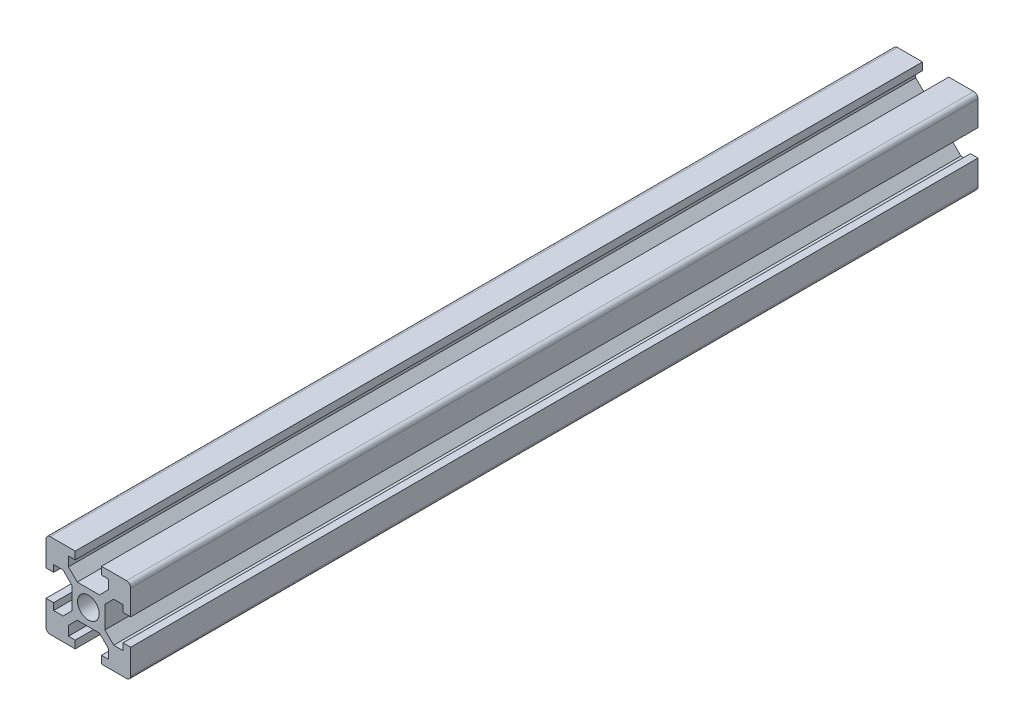
SolidWorks part; units mm, degrees
ref_plane "前视基准面" through (0, 0, 0) normal (0, 0, 1) x (1, 0, 0)
ref_plane "上视基准面" through (0, 0, 0) normal (0, 1, 0) x (1, 0, 0)
ref_plane "右视基准面" through (0, 0, 0) normal (1, 0, 0) x (0, 0, -1)
sketch "草图1" plane through (0, 0, 0) normal (0, 0, 1) x (1, 0, 0)
  line L0 (4.6219, 1.9053) -> (6.6947, 3.9781)
  line L1 (-8.0053, 8.0053) -> (-1.1053, 8.0053)
  line L2 (-8.0053, 8.0053) -> (-8.0053, 1.1053)
  line L3 (-8.0053, -11.9947) -> (-1.1053, -11.9947)
  line L4 (11.9947, 8.0053) -> (11.9947, 1.1053)
  line L5 (-8.0053, 8.0053) -> (11.9947, -11.9947) construction
  line L6 (5.8947, 0.6325) -> (7.9675, 2.7053)
  line L7 (-0.6325, -5.8947) -> (4.6219, -5.8947)
  line L8 (-1.9053, -4.6219) -> (-1.9053, 0.6325)
  line L9 (-0.6325, 1.9053) -> (4.6219, 1.9053)
  line L10 (5.8947, -4.6219) -> (5.8947, 0.6325)
  line L11 (-2.53, -6.5195) -> (5.8947, 1.9053) construction
  line L12 (-2.53, 2.53) -> (5.8947, -5.8947) construction
  line L13 (7.9675, 2.7053) -> (10.1947, 2.7053)
  line L14 (6.6947, 3.9781) -> (6.6947, 6.2053)
  line L15 (6.6947, 6.2053) -> (5.0947, 6.2053)
  line L16 (5.0947, 6.2053) -> (5.0947, 8.0053)
  line L17 (10.1947, 2.7053) -> (10.1947, 1.1053)
  line L18 (10.1947, 1.1053) -> (11.9947, 1.1053)
  line L19 (1.9947, -1.9947) -> (1.9947, 14.4959) construction
  line L20 (-6.2053, 1.1053) -> (-8.0053, 1.1053)
  line L21 (-6.2053, 2.7053) -> (-6.2053, 1.1053)
  line L22 (-1.9053, 0.6325) -> (-3.9781, 2.7053)
  line L23 (-3.9781, 2.7053) -> (-6.2053, 2.7053)
  line L24 (-2.7053, 3.9781) -> (-2.7053, 6.2053)
  line L25 (-0.6325, 1.9053) -> (-2.7053, 3.9781)
  line L26 (-2.7053, 6.2053) -> (-1.1053, 6.2053)
  line L27 (-1.1053, 6.2053) -> (-1.1053, 8.0053)
  line L28 (1.9947, -1.9947) -> (-12.4459, -1.9947) construction
  line L29 (-1.9053, -4.6219) -> (-3.9781, -6.6947)
  line L30 (-0.6325, -5.8947) -> (-2.7053, -7.9675)
  line L31 (4.6219, -5.8947) -> (6.6947, -7.9675)
  line L32 (5.8947, -4.6219) -> (7.9675, -6.6947)
  line L33 (-6.2053, -5.0947) -> (-8.0053, -5.0947)
  line L34 (10.1947, -5.0947) -> (11.9947, -5.0947)
  line L35 (-1.1053, -10.1947) -> (-1.1053, -11.9947)
  line L36 (5.0947, -10.1947) -> (5.0947, -11.9947)
  line L37 (-2.7053, -10.1947) -> (-1.1053, -10.1947)
  line L38 (-2.7053, -7.9675) -> (-2.7053, -10.1947)
  line L39 (-3.9781, -6.6947) -> (-6.2053, -6.6947)
  line L40 (-6.2053, -6.6947) -> (-6.2053, -5.0947)
  line L41 (10.1947, -6.6947) -> (10.1947, -5.0947)
  line L42 (6.6947, -10.1947) -> (5.0947, -10.1947)
  line L43 (6.6947, -7.9675) -> (6.6947, -10.1947)
  line L44 (7.9675, -6.6947) -> (10.1947, -6.6947)
  line L45 (11.9947, -5.0947) -> (11.9947, -11.9947)
  line L46 (5.0947, 8.0053) -> (11.9947, 8.0053)
  line L47 (-8.0053, -5.0947) -> (-8.0053, -11.9947)
  line L48 (5.0947, -11.9947) -> (11.9947, -11.9947)
  circle A0 centre (1.9947, -1.9947) radius 2.55
  point P0 (0, 0)
  point P6 (1.9947, -1.9947)
  dimension "D4" = 5.1
  dimension "D1" = 20
  dimension "D2" = 20
  dimension "D3" = 7.8
  dimension "D5" = 6.2
  dimension "D6" = 9.4
  dimension "D7" = 0.9
  dimension "D8" = 1.8
extrude "凸台-拉伸1" add sketch "草图1" along normal blind 200
fillet "圆角1" radius 1 4 edges at (11.9947, -11.9947, 100) (-8.0053, -11.9947, 100) (11.9947, 8.0053, 100) (-8.0053, 8.0053, 100)
